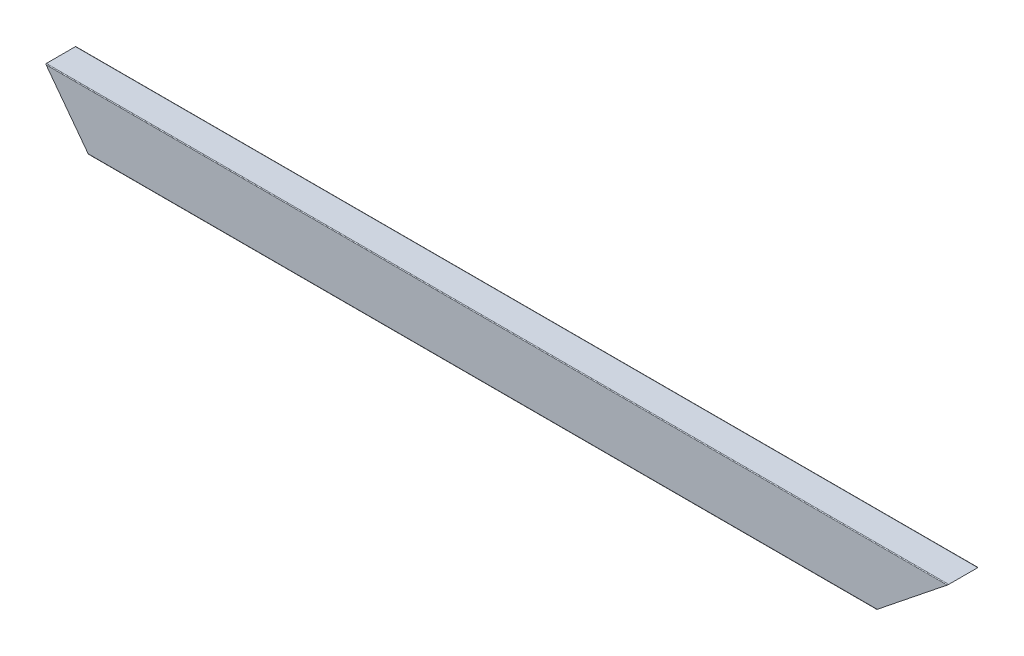
SolidWorks part; units mm, degrees
ref_plane "Front Plane" through (0, 0, 0) normal (0, 0, 1) x (1, 0, 0)
ref_plane "Top Plane" through (0, 0, 0) normal (0, 1, 0) x (1, 0, 0)
ref_plane "Right Plane" through (0, 0, 0) normal (1, 0, 0) x (0, 0, -1)
sketch "Sketch2" plane through (0, 0, 0) normal (0, 0, 1) x (1, 0, 0)
  line L0 (-349.25, -25.4) -> (-387.3834, 25.4)
  line L1 (-349.25, 25.4) -> (349.25, 25.4)
  line L3 (-349.25, -25.4) -> (349.25, -25.4)
  line L5 (-349.25, 25.4) -> (349.25, -25.4) construction
  line L6 (-349.25, -25.4) -> (349.25, 25.4) construction
  line L7 (-387.3834, 25.4) -> (-349.25, 25.4)
  line L8 (349.25, -25.4) -> (412.75, 25.4)
  line L9 (412.75, 25.4) -> (349.25, 25.4)
  point P0 (0, 0)
extrude "Boss-Extrude1" add sketch "Sketch2" along normal blind 13.4937 and the other way blind 13.4937
sketch "Sketch3" plane through (0, 0, 0) normal (1, 0, 0) x (0, 0, -1)
  line L1 (-11.807, 23.6141) -> (11.807, 23.6141)
  line L2 (-11.807, 23.6141) -> (-11.807, -23.6141)
  line L3 (-11.807, -23.6141) -> (11.807, -23.6141)
  line L4 (11.807, 23.6141) -> (11.807, -23.6141)
  line L5 (-11.807, 23.6141) -> (11.807, -23.6141) construction
  line L6 (-11.807, -23.6141) -> (11.807, 23.6141) construction
  point P0 (0, 0)
extrude "Cut-Extrude1" cut sketch "Sketch3" against normal through all and the other way through all contours L2 L1 L4 L3
fillet "Fillet1" radius 1.27 4 edges at (0.4459, -23.6141, -11.807) (0.4459, -23.6141, 11.807) (12.2374, 23.6141, 11.807) (12.2374, 23.6141, -11.807)
fillet "Fillet2" radius 0.635 4 edges at (0, -25.4, 13.4937) (0, -25.4, -13.4937) (12.6833, 25.4, -13.4937) (12.6833, 25.4, 13.4937)
